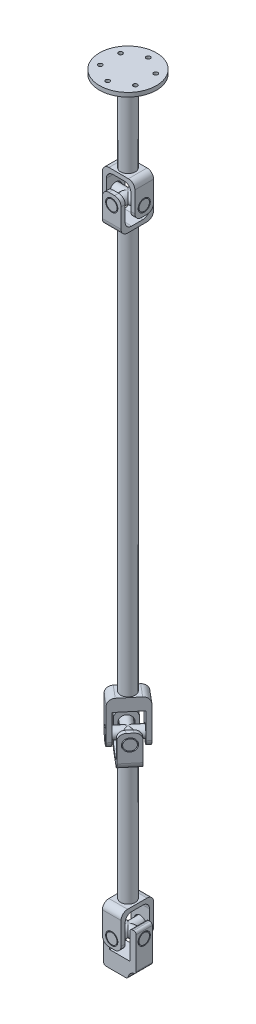
SolidWorks part; units mm, degrees
other "SC_E1"
other "UniJoint_1"
other "SC_E2"
other "SC_E3"
other "SC_E4"
other "UniJoint_2"
other "UniJoint_3"
ref_plane "Front Plane" through (0, 0, 0) normal (0, 0, 1) x (1, 0, 0)
ref_plane "Top Plane" through (0, 0, 0) normal (0, 1, 0) x (1, 0, 0)
ref_plane "Right Plane" through (0, 0, 0) normal (1, 0, 0) x (0, 0, -1)
sketch "Sketch2" plane through (0, 0, 0) normal (0, 1, 0) x (1, 0, 0)
  line L1 (20, -10) -> (-20, -10)
  line L2 (20, -10) -> (20, 10)
  line L3 (20, 10) -> (-20, 10)
  line L4 (-20, -10) -> (-20, 10)
  line L5 (20, -10) -> (-20, 10) construction
  line L6 (20, 10) -> (-20, -10) construction
  point P0 (0, 0)
  dimension "D1" = 40
  dimension "D2" = 20
extrude "Boss-Extrude1" add sketch "Sketch2" along normal blind 55
sketch "Sketch3" plane through (20, 0, 0) normal (1, 0, 0) x (0, 0, -1)
  line L0 (0, 43) -> (0, 55) construction
  line L1 (-10, 55) -> (10, 55) construction
  circle A0 centre (0, 43) radius 7.5
  dimension "D1" = 15
  dimension "D2" = 12
extrude "Cut-Extrude1" cut sketch "Sketch3" against normal through all
sketch "Sketch4" plane through (0, 0, 10) normal (0, 0, 1) x (1, 0, 0)
  line L0 (-20, 55) -> (20, 55) construction
  line L1 (-12.5, 55) -> (12.5, 55)
  line L2 (-12.5, 55) -> (-12.5, 20)
  line L3 (-12.5, 20) -> (12.5, 20)
  line L4 (12.5, 55) -> (12.5, 20)
  line L5 (-12.5, 37.5) -> (-20, 37.5) construction
  line L6 (-20, 55) -> (-20, 0) construction
  line L7 (12.5, 37.5) -> (20, 37.5) construction
  line L8 (20, 55) -> (20, 0) construction
  line L9 (20, 0) -> (20, 10)
  line L10 (20, 0) -> (10, 0)
  arc A0 (20, 10) -> (10, 0) centre (20, 0) ccw
  dimension "D3" = 20
  dimension "D1" = 25
  dimension "D2" = 35
extrude "Cut-Extrude2" cut sketch "Sketch4" against normal through all
fillet "Fillet1" radius 3 7 edges at (20, 55, 0) (-20, 55, 0) (10, 0, 0) (20, 10, 0) (-20, 0, 0) (12.5, 55, 0) (-12.5, 55, 0)
sketch "Sketch23" plane through (0, 0, 0) normal (0, -1, 0) x (1, 0, 0)
  line L0 (-17, 0) -> (7.3509, 0) construction
  line L1 (-17, 10) -> (-17, -10) construction
  line L2 (7.3509, -10) -> (7.3509, 10) construction
  line L3 (-4.8246, 10) -> (-4.8246, -10) construction
  line L4 (-17, 10) -> (7.3509, 10) construction
  line L5 (7.3509, -10) -> (-17, -10) construction
  circle A0 centre (-4.8246, 0) radius 5
  dimension "D1" = 10
extrude "Cut-Extrude8" cut sketch "Sketch23" against normal blind 10
sketch "Sketch5" plane through (-20, 0, 0) normal (-1, 0, 0) x (0, 0, 1)
  circle A0 centre (0, 43) radius 7.5 construction
  circle A1 centre (0, 43) radius 7.5 construction
  circle A2 centre (0, 43) radius 6.5
  dimension "D1" = 1
extrude "Boss-Extrude2" add sketch "Sketch5" against normal blind 40 separate body
sketch "Sketch6" plane through (0, 0, 0) normal (0, 0, 1) x (1, 0, 0)
  line L1 (-20, 36.5) -> (20, 36.5) construction
  line L2 (20, 49.5) -> (-20, 49.5) construction
  line L3 (-20, 43) -> (20, 43) construction
  line L4 (-20, 49.5) -> (-20, 36.5) construction
  line L5 (20, 36.5) -> (20, 49.5) construction
  circle A0 centre (0, 43) radius 6.5
extrude "Boss-Extrude3" add sketch "Sketch6" along normal mid plane 40
sketch "Sketch7" plane through (0, 0, 0) normal (1, 0, 0) x (0, 0, -1)
  line L0 (0, 43) -> (-15, 43) construction
  line L1 (-20, 32.5) -> (-15, 32.5)
  line L2 (-20, 32.5) -> (-20, 76)
  line L4 (-15, 32.5) -> (-15, 71)
  line L5 (15, 32.5) -> (20, 32.5)
  line L6 (15, 32.5) -> (15, 71)
  line L8 (20, 32.5) -> (20, 76)
  line L9 (-15, 71) -> (15, 71)
  line L11 (-20, 76) -> (20, 76)
  line L13 (0, 43) -> (15, 43) construction
  dimension "D1" = 5
  dimension "D2" = 40
  dimension "D3" = 4
  dimension "D4" = 28
  dimension "D5" = 5
extrude "Boss-Extrude4" add sketch "Sketch7" along normal mid plane 23 separate body
sketch "Sketch12" plane through (0, 0, -20) normal (0, 0, -1) x (-1, 0, 0)
  circle A0 centre (0, 43) radius 7.5
  circle A1 centre (0, 43) radius 6.5
  circle A2 centre (0, 43) radius 6.5 construction
  dimension "D2" = 1
  dimension "D1" = 0
extrude "Cut-Extrude4" cut sketch "Sketch12" against normal through all
sketch "Sketch8" plane through (0, 76, 0) normal (0, 1, 0) x (1, 0, 0)
  line L0 (0, 20) -> (0, -20) construction
  line L1 (11.5, 20) -> (-11.5, 20) construction
  line L2 (11.5, -20) -> (-11.5, -20) construction
  line L3 (11.5, 0) -> (-11.5, 0) construction
  line L4 (11.5, 20) -> (11.5, -20) construction
  line L5 (-11.5, 20) -> (-11.5, -20) construction
  circle A0 centre (0, 0) radius 9
  dimension "D1" = 18
extrude "Boss-Extrude5" add sketch "Sketch8" along normal blind 150
sketch "Sketch9" plane through (0, 226, 0) normal (0, 1, 0) x (1, 0, 0)
  line L0 (15.3209, -12.8558) -> (-15.3209, 12.8558) construction
  line L1 (-7.9288, 21.6653) -> (-22.7129, 4.0462)
  line L2 (7.9288, -21.6653) -> (22.7129, -4.0462)
  line L3 (-7.9288, 21.6653) -> (22.7129, -4.0462)
  line L4 (-22.7129, 4.0462) -> (7.9288, -21.6653)
  line L5 (0, 0) -> (-7.5335, 0) construction
  point P3 (0, 0)
  point P8 (-15.3209, 12.8558)
  point P11 (15.3209, -12.8558)
  dimension "D1" = 23
  dimension "D2" = 40
  dimension "D3" = 40
extrude "Boss-Extrude6" add sketch "Sketch9" along normal blind 5
sketch "Sketch10" plane through (0, 231, 0) normal (0, 1, 0) x (1, 0, 0)
  line L0 (7.9288, -21.6653) -> (22.7129, -4.0462) construction
  line L1 (-7.9288, 21.6653) -> (-22.7129, 4.0462) construction
  line L2 (7.9288, -21.6653) -> (22.7129, -4.0462)
  line L3 (-7.9288, 21.6653) -> (-22.7129, 4.0462)
  line L4 (-4.0986, 18.4513) -> (-18.8827, 0.8323)
  line L5 (4.0986, -18.4513) -> (18.8827, -0.8323)
  line L6 (-22.7129, 4.0462) -> (-18.8827, 0.8323)
  line L7 (-7.9288, 21.6653) -> (-4.0986, 18.4513)
  line L8 (18.8827, -0.8323) -> (22.7129, -4.0462)
  line L9 (4.0986, -18.4513) -> (7.9288, -21.6653)
  dimension "D1" = 5
extrude "Boss-Extrude7" add sketch "Sketch10" along normal blind 35
sketch "Sketch11" plane through (15.3209, 0, 12.8558) normal (0.766, 0, 0.6428) x (0.6428, 0, -0.766)
  line L0 (0, 253.5) -> (0, 266) construction
  line L1 (-11.5, 266) -> (11.5, 266) construction
  circle A0 centre (0, 253.5) radius 7.5
  dimension "D1" = 15
  dimension "D2" = 12.5
extrude "Cut-Extrude3" cut sketch "Sketch11" against normal through all
fillet "Fillet2" radius 8 16 edges at (11.5, 32.5, -17.5) (11.5, 32.5, 17.5) (-11.5, 32.5, 17.5) (-11.5, 32.5, -17.5) (0, 76, -20) (0, 76, 20) (-15.3209, 226, -12.8558) (15.3209, 226, 12.8558) (-6.0137, 266, -20.0583) (20.7978, 266, 2.4393) (6.0137, 266, 20.0583) (-20.7978, 266, -2.4393) (0, 71, -15) (0, 71, 15) (11.4907, 231, 9.6418) (-11.4907, 231, -9.6418)
sketch "Sketch24" plane through (15.3209, 0, 12.8558) normal (0.766, 0, 0.6428) x (0.6428, 0, -0.766)
  circle A0 centre (0, 253.5) radius 7.5 construction
  circle A1 centre (0, 253.5) radius 7.5 construction
  circle A2 centre (0, 253.5) radius 6.5
  dimension "D1" = 1
extrude "Boss-Extrude15" add sketch "Sketch24" against normal blind 40 separate body
ref_plane "Plane3" through (0, 0, 0) normal (-0.6428, 0, 0.766) x (0.766, 0, 0.6428)
sketch "Sketch25" plane through (0, 0, 0) normal (-0.6428, 0, 0.766) x (0.766, 0, 0.6428)
  line L0 (-20, 253.5) -> (20, 253.5) construction
  line L1 (-20, 260) -> (-20, 247) construction
  line L2 (20, 247) -> (20, 260) construction
  line L3 (-20, 247) -> (20, 247) construction
  line L4 (20, 260) -> (-20, 260) construction
  circle A0 centre (0, 253.5) radius 6.5
extrude "Boss-Extrude16" add sketch "Sketch25" along normal mid plane 40
ref_plane "Plane1" through (0, 0, 0) normal (-0.766, 0, -0.6428) x (-0.6428, 0, 0.766)
sketch "Sketch13" plane through (0, 0, 0) normal (-0.766, 0, -0.6428) x (-0.6428, 0, 0.766)
  line L0 (-15, 242) -> (-15, 282)
  line L5 (0, 246) -> (0, 242) construction
  line L6 (-20, 242) -> (-15, 242)
  line L8 (-20, 242) -> (-20, 297)
  line L9 (-20, 297) -> (20, 297)
  line L10 (20, 242) -> (20, 297)
  line L11 (-15, 282) -> (15, 282)
  line L12 (15, 282) -> (15, 242)
  line L13 (15, 242) -> (20, 242)
  line L14 (0, 253.5) -> (-15, 253.5) construction
  line L15 (0, 253.5) -> (15, 253.5) construction
  circle A0 centre (0, 253.5) radius 7.5 construction
  circle A1 centre (0, 253.5) radius 7.5 construction
  dimension "D1" = 40
  dimension "D2" = 5
  dimension "D3" = 55
  dimension "D4" = 15
  dimension "D5" = 30
  dimension "D6" = 4
extrude "Boss-Extrude8" add sketch "Sketch13" along normal mid plane 20 separate body
sketch "Sketch14" plane through (0, 297, 0) normal (0, 1, 0) x (1, 0, 0)
  circle A0 centre (0, 0) radius 9
  dimension "D1" = 18
extrude "Boss-Extrude9" add sketch "Sketch14" along normal blind 500
sketch "Sketch15" plane through (0, 797, 0) normal (0, 1, 0) x (1, 0, 0)
  line L1 (11.5, -20) -> (-11.5, -20)
  line L2 (11.5, -20) -> (11.5, 20)
  line L3 (11.5, 20) -> (-11.5, 20)
  line L4 (-11.5, -20) -> (-11.5, 20)
  line L5 (11.5, -20) -> (-11.5, 20) construction
  line L6 (11.5, 20) -> (-11.5, -20) construction
  point P0 (0, 0)
  dimension "D1" = 23
  dimension "D2" = 40
extrude "Boss-Extrude10" add sketch "Sketch15" along normal blind 5
sketch "Sketch16" plane through (0, 802, 0) normal (0, 1, 0) x (1, 0, 0)
  line L0 (11.5, -20) -> (11.5, 20) construction
  line L1 (-11.5, 20) -> (11.5, 20)
  line L2 (-11.5, 20) -> (-11.5, 15)
  line L3 (-11.5, 15) -> (11.5, 15)
  line L4 (11.5, 20) -> (11.5, 15)
  line L5 (-11.5, 20) -> (-11.5, -20) construction
  line L6 (11.5, -20) -> (-11.5, -20)
  line L7 (11.5, -20) -> (11.5, -15)
  line L8 (11.5, -15) -> (-11.5, -15)
  line L9 (-11.5, -20) -> (-11.5, -15)
  dimension "D1" = 5
extrude "Boss-Extrude11" add sketch "Sketch16" along normal blind 35
sketch "Sketch17" plane through (0, 0, 20) normal (0, 0, 1) x (1, 0, 0)
  line L0 (-11.5, 837) -> (11.5, 837) construction
  line L1 (0, 837) -> (0, 825) construction
  circle A0 centre (0, 825) radius 7.5
  dimension "D1" = 12
  dimension "D2" = 15
extrude "Cut-Extrude5" cut sketch "Sketch17" against normal through all
fillet "Fillet3" radius 8 14 edges at (-12.8558, 297, 15.3209) (-18.9092, 242, 6.9779) (-3.5883, 242, 19.8337) (18.9092, 242, -6.9779) (3.5883, 242, -19.8337) (12.8558, 297, -15.3209) (11.5, 837, -17.5) (11.5, 837, 17.5) (-11.5, 837, 17.5) (-11.5, 837, -17.5) (0, 802, -15) (0, 797, -20) (0, 802, 15) (0, 797, 20)
sketch "Sketch21" plane through (-12.8558, 0, 15.3209) normal (-0.6428, 0, 0.766) x (0.766, 0, 0.6428)
  line L0 (0, 246) -> (0, 242) construction
  line L1 (-2, 242) -> (2, 242) construction
  circle A0 centre (0, 253.5) radius 7.5
  dimension "D2" = 15
  dimension "D1" = 4
extrude "Cut-Extrude6" cut sketch "Sketch21" against normal through all
sketch "Sketch26" plane through (0, 0, 20) normal (0, 0, 1) x (1, 0, 0)
  circle A0 centre (0, 825) radius 7.5 construction
  circle A1 centre (0, 825) radius 7.5 construction
  circle A2 centre (0, 825) radius 6.5
  dimension "D1" = 1
extrude "Boss-Extrude17" add sketch "Sketch26" against normal blind 40 separate body
ref_plane "Plane4" through (0, 0, 0) normal (-1, 0, 0) x (0, 0, 1)
sketch "Sketch27" plane through (0, 0, 0) normal (-1, 0, 0) x (0, 0, 1)
  line L0 (-20, 825) -> (20, 825) construction
  line L1 (-20, 831.5) -> (-20, 818.5) construction
  line L2 (20, 818.5) -> (20, 831.5) construction
  line L3 (20, 831.5) -> (-20, 831.5) construction
  circle A0 centre (0, 825) radius 6.5
extrude "Boss-Extrude18" add sketch "Sketch27" along normal mid plane 40
ref_plane "Plane2" through (0, 0, 0) normal (0, 0, -1) x (-1, 0, 0)
sketch "Sketch18" plane through (0, 0, 0) normal (0, 0, -1) x (-1, 0, 0)
  line L0 (-15, 813.5) -> (-15, 850)
  line L1 (-20, 813.5) -> (-15, 813.5)
  line L2 (-20, 813.5) -> (-20, 855)
  line L3 (-20, 855) -> (20, 855)
  line L4 (20, 813.5) -> (20, 855)
  line L5 (-15, 850) -> (15, 850)
  line L6 (15, 850) -> (15, 813.5)
  line L7 (15, 813.5) -> (20, 813.5)
  line L8 (0, 825) -> (-15, 825) construction
  line L9 (0, 825) -> (15, 825) construction
  line L10 (0, 817.5) -> (0, 813.5) construction
  circle A0 centre (0, 825) radius 7.5 construction
  circle A1 centre (0, 825) radius 7.5 construction
  dimension "D1" = 40
  dimension "D2" = 4
  dimension "D3" = 5
  dimension "D4" = 5
  dimension "D5" = 25
extrude "Boss-Extrude12" add sketch "Sketch18" along normal mid plane 23 separate body
sketch "Sketch19" plane through (0, 855, 0) normal (0, 1, 0) x (1, 0, 0)
  circle A0 centre (0, 0) radius 9
  dimension "D1" = 18
extrude "Boss-Extrude13" add sketch "Sketch19" along normal blind 100
fillet "Fillet4" radius 8 8 edges at (20, 855, 0) (15, 850, 0) (-15, 850, 0) (17.5, 813.5, 11.5) (17.5, 813.5, -11.5) (-17.5, 813.5, 11.5) (-17.5, 813.5, -11.5) (-20, 855, 0)
sketch "Sketch20" plane through (0, 955, 0) normal (0, 1, 0) x (1, 0, 0)
  line L0 (0, 0) -> (0, 35) construction
  circle A0 centre (0, 0) radius 35
  circle A1 centre (0, 25) radius 2.5
  circle A2 centre (21.6506, 12.5) radius 2.5
  circle A3 centre (21.6506, -12.5) radius 2.5
  circle A4 centre (0, -25) radius 2.5
  circle A5 centre (-21.6506, -12.5) radius 2.5
  circle A6 centre (-21.6506, 12.5) radius 2.5
  point P18 (0, 0)
  dimension "D1" = 70
  dimension "D2" = 5
  dimension "D3" = 25
  dimension "D4" = 6
extrude "Boss-Extrude14" add sketch "Sketch20" along normal blind 5
sketch "Sketch22" plane through (-20, 0, 0) normal (-1, 0, 0) x (0, 0, 1)
  line L0 (0, 817.5) -> (0, 813.5) construction
  line L1 (-3.5, 813.5) -> (3.5, 813.5) construction
  circle A0 centre (0, 825) radius 7.5
  dimension "D2" = 15
  dimension "D1" = 4
extrude "Cut-Extrude7" cut sketch "Sketch22" against normal through all
other "Save Bodies1"
